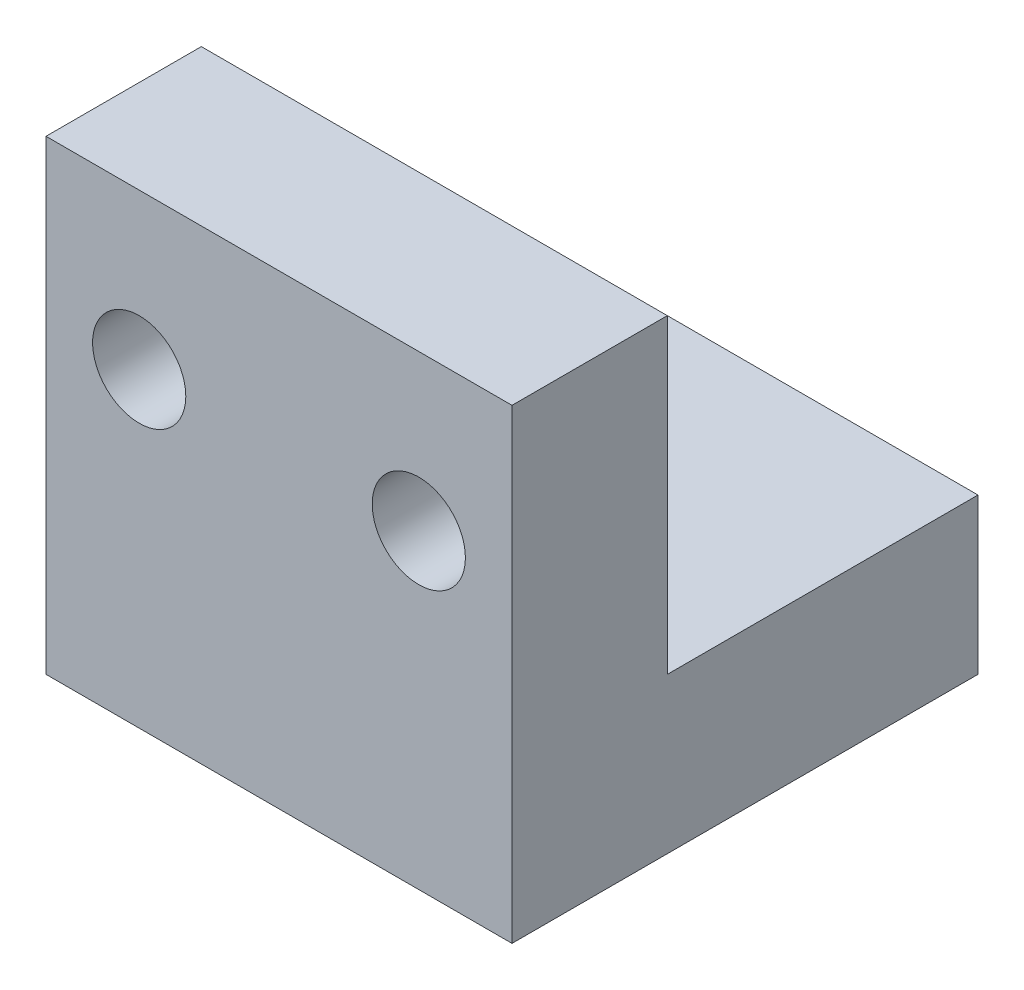
SolidWorks part; units mm, degrees
ref_plane "前视基准面" through (0, 0, 0) normal (0, 0, 1) x (1, 0, 0)
ref_plane "上视基准面" through (0, 0, 0) normal (0, 1, 0) x (1, 0, 0)
ref_plane "右视基准面" through (0, 0, 0) normal (1, 0, 0) x (0, 0, -1)
sketch "草图1" plane through (0, 0, 0) normal (0, 1, 0) x (1, 0, 0)
  line L1 (0, 0) -> (15, 0)
  line L2 (0, 0) -> (0, 15)
  line L3 (0, 15) -> (15, 15)
  line L4 (15, 0) -> (15, 15)
  circle A0 centre (7.5, 10) radius 1.5
  dimension "D3" = 7.5
  dimension "D4" = 5
  dimension "D5" = 3
  dimension "D1" = 15
  dimension "D2" = 15
extrude "凸台-拉伸1" add sketch "草图1" along normal blind 5
sketch "草图2" plane through (0, 0, 0) normal (0, 0, 1) x (1, 0, 0)
  line L0 (0, 0) -> (15, 0) construction
  line L1 (0, 0) -> (15, 0)
  line L2 (0, 0) -> (0, 15)
  line L3 (0, 15) -> (15, 15)
  line L4 (15, 0) -> (15, 15)
  line L6 (0, 5) -> (0, 0) construction
  circle A0 centre (3, 10) radius 1.5
  circle A1 centre (12, 10) radius 1.5
  dimension "D3" = 3
  dimension "D4" = 5
  dimension "D5" = 3
  dimension "D6" = 3
  dimension "D7" = 5
  dimension "D1" = 15
  dimension "D2" = 15
extrude "凸台-拉伸2" add sketch "草图2" against normal blind 5
